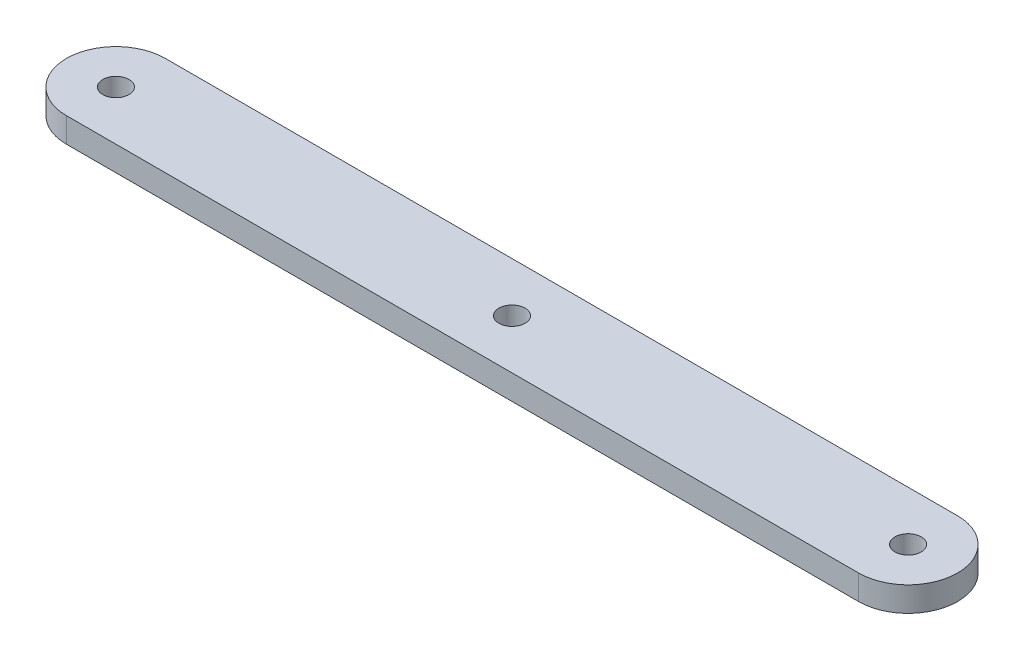
SolidWorks part; units mm, degrees
ref_plane "Front Plane" through (0, 0, 0) normal (0, 0, 1) x (1, 0, 0)
ref_plane "Top Plane" through (0, 0, 0) normal (0, 1, 0) x (1, 0, 0)
ref_plane "Right Plane" through (0, 0, 0) normal (1, 0, 0) x (0, 0, -1)
sketch "Sketch1" plane through (0, 0, 0) normal (0, 1, 0) x (1, 0, 0)
  line L0 (-101.6, 0) -> (101.6, 0) construction
  line L1 (-101.6, 12.7) -> (101.6, 12.7)
  line L2 (-101.6, -12.7) -> (101.6, -12.7)
  arc A0 (-101.6, 12.7) -> (-101.6, -12.7) centre (-101.6, 0) ccw
  arc A1 (101.6, -12.7) -> (101.6, 12.7) centre (101.6, 0) ccw
  circle A2 centre (101.6, 0) radius 3.3655
  circle A3 centre (-101.6, 0) radius 3.3655
  circle A4 centre (0, 0) radius 3.3655
  point P2 (0, 0)
  dimension "D3" = 6.731
  dimension "D5" = 6.731
  dimension "D6" = 6.731
  dimension "D1" = 203.2
  dimension "D2" = 25.4
  dimension "D4" = 0
extrude "Boss-Extrude1" add sketch "Sketch1" along normal blind 6.35
